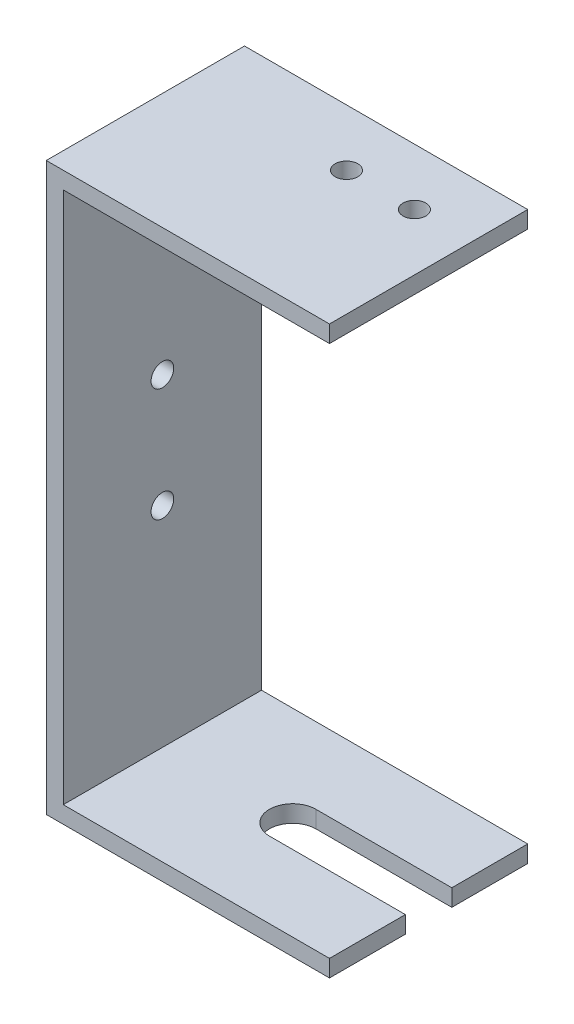
SolidWorks part; units mm, degrees
ref_plane "Front Plane" through (0, 0, 0) normal (0, 0, 1) x (1, 0, 0)
ref_plane "Top Plane" through (0, 0, 0) normal (0, 1, 0) x (1, 0, 0)
ref_plane "Right Plane" through (0, 0, 0) normal (1, 0, 0) x (0, 0, -1)
sketch "Sketch1" plane through (0, 0, 0) normal (0, 0, 1) x (1, 0, 0)
  line L0 (0, 0) -> (-50, 0)
  line L1 (-50, 0) -> (-50, 100)
  line L2 (-50, 100) -> (0, 100)
  line L3 (0, 3) -> (-47, 3)
  line L4 (-47, 3) -> (-47, 97)
  line L5 (-47, 97) -> (0, 97)
  line L6 (0, 100) -> (0, 97)
  line L7 (0, 3) -> (0, 0)
  dimension "D1" = 3
  dimension "D2" = 50
  dimension "D3" = 100
extrude "Boss-Extrude1" add sketch "Sketch1" along normal blind 35
sketch "Sketch2" plane through (0, 0, 0) normal (0, -1, 0) x (1, 0, 0)
  line L0 (0, 13.4) -> (-24, 13.4)
  line L1 (0, 35) -> (0, 0) construction
  line L2 (-24, 21.6) -> (0, 21.6)
  line L3 (0, 21.6) -> (0, 13.4)
  arc A0 (-24, 13.4) -> (-24, 21.6) centre (-24, 17.5) cw
  point P8 (0, 17.5)
  point P9 (0, 17.5)
  dimension "D1" = 8.2
  dimension "D2" = 24
extrude "Cut-Extrude1" cut sketch "Sketch2" against normal up to next
sketch "Sketch3" plane through (0, 100, 0) normal (0, 1, 0) x (1, 0, 0)
  line L1 (0, -35) -> (0, 0) construction
  line L2 (0, 0) -> (-50, 0) construction
  circle A0 centre (-22, -10) radius 2
  circle A1 centre (-10, -10) radius 2
  dimension "D1" = 12
  dimension "D2" = 4
  dimension "D4" = 10
  dimension "D3" = 10
extrude "Cut-Extrude2" cut sketch "Sketch3" against normal up to next
sketch "Sketch4" plane through (-50, 0, 0) normal (-1, 0, 0) x (0, 0, 1)
  line L2 (0, 100) -> (0, 0) construction
  line L3 (35, 100) -> (0, 100) construction
  circle A0 centre (17.5, 60) radius 2
  circle A1 centre (17.5, 40) radius 2
  point P6 (0, 50)
  point P12 (17.5, 100)
  dimension "D1" = 4
  dimension "D2" = 10
  dimension "D3" = 20
extrude "Cut-Extrude3" cut sketch "Sketch4" against normal up to next
